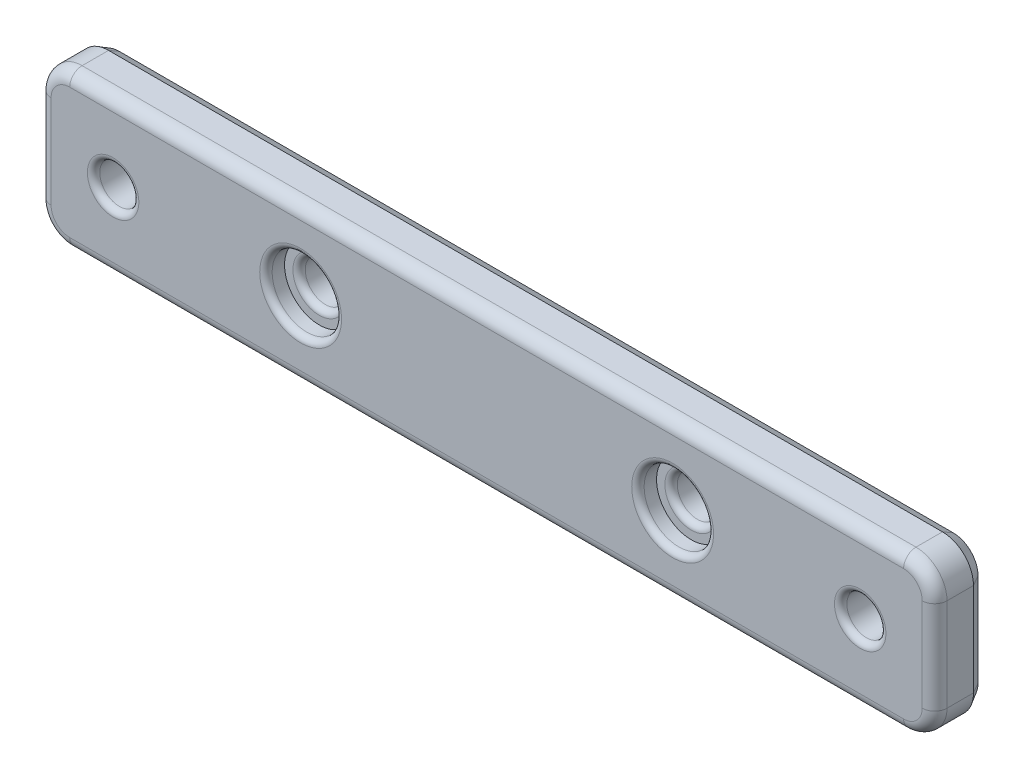
SolidWorks part; units mm, degrees
ref_plane "Front Plane" through (0, 0, 0) normal (0, 0, 1) x (1, 0, 0)
ref_plane "Top Plane" through (0, 0, 0) normal (0, 1, 0) x (1, 0, 0)
ref_plane "Right Plane" through (0, 0, 0) normal (1, 0, 0) x (0, 0, -1)
sketch "Sketch2" plane through (0, 0, 0) normal (0, 0, 1) x (1, 0, 0)
  line L1 (-72.25, -12.5) -> (72.25, -12.5)
  line L2 (-72.25, -12.5) -> (-72.25, 12.5)
  line L3 (-72.25, 12.5) -> (72.25, 12.5)
  line L4 (72.25, -12.5) -> (72.25, 12.5)
  line L5 (-72.25, -12.5) -> (72.25, 12.5) construction
  line L6 (-72.25, 12.5) -> (72.25, -12.5) construction
  point P0 (0, 0)
  dimension "D1" = 144.5
  dimension "D2" = 25
extrude "Boss-Extrude1" add sketch "Sketch2" along normal blind 8
sketch "Sketch3" plane through (0, 0, 8) normal (0, 0, 1) x (1, 0, 0)
  line L0 (-72.25, 12.5) -> (-72.25, -12.5) construction
  line L1 (-60.25, 0) -> (-30, 0) construction
  line L2 (30, 0) -> (60.25, 0) construction
  line L6 (30, 0) -> (-30, 0) construction
  circle A0 centre (-60.25, 0) radius 3.15
  circle A1 centre (60.25, 0) radius 3.15
  circle A5 centre (-30, 0) radius 3.25
  circle A6 centre (30, 0) radius 3.25
  dimension "D1" = 6.3
  dimension "D2" = 6.5
  dimension "D3" = 12
  dimension "D4" = 120.5
  dimension "D6" = 60
extrude "Cut-Extrude1" cut sketch "Sketch3" against normal through all
sketch "Sketch4" plane through (0, 0, 8) normal (0, 0, 1) x (1, 0, 0)
  circle A0 centre (-30, 0) radius 5.6
  circle A1 centre (30, 0) radius 5.6
  dimension "D1" = 11.2
extrude "Cut-Extrude2" cut sketch "Sketch4" against normal blind 3
fillet "Fillet1" radius 5 4 edges at (-72.25, -12.5, 4) (-72.25, 12.5, 4) (72.25, -12.5, 4) (72.25, 12.5, 4)
fillet "Fillet2" radius 2 8 edges at (70.7855, 11.0355, 8) (72.25, 0, 8) (70.7855, -11.0355, 8) (0, -12.5, 8) (-70.7855, -11.0355, 8) (-72.25, 0, 8) (-70.7855, 11.0355, 8) (0, 12.5, 8)
fillet "Fillet3" radius 1 6 edges at (63.4, 0, 8) (-57.1, 0, 8) (33.25, 0, 5) (-26.75, 0, 5) (35.6, 0, 8) (-24.4, 0, 8)
chamfer "Chamfer1" distance 1 angle 60 8 edges at (0, 12.5, 0) (-70.7855, 11.0355, 0) (70.7855, 11.0355, 0) (-72.25, 0, 0) (72.25, 0, 0) (-70.7855, -11.0355, 0) (70.7855, -11.0355, 0) (0, -12.5, 0)
chamfer "Chamfer2" distance 1 angle 30 4 edges at (63.4, 0, 0) (33.25, 0, 0) (-26.75, 0, 0) (-57.1, 0, 0)
